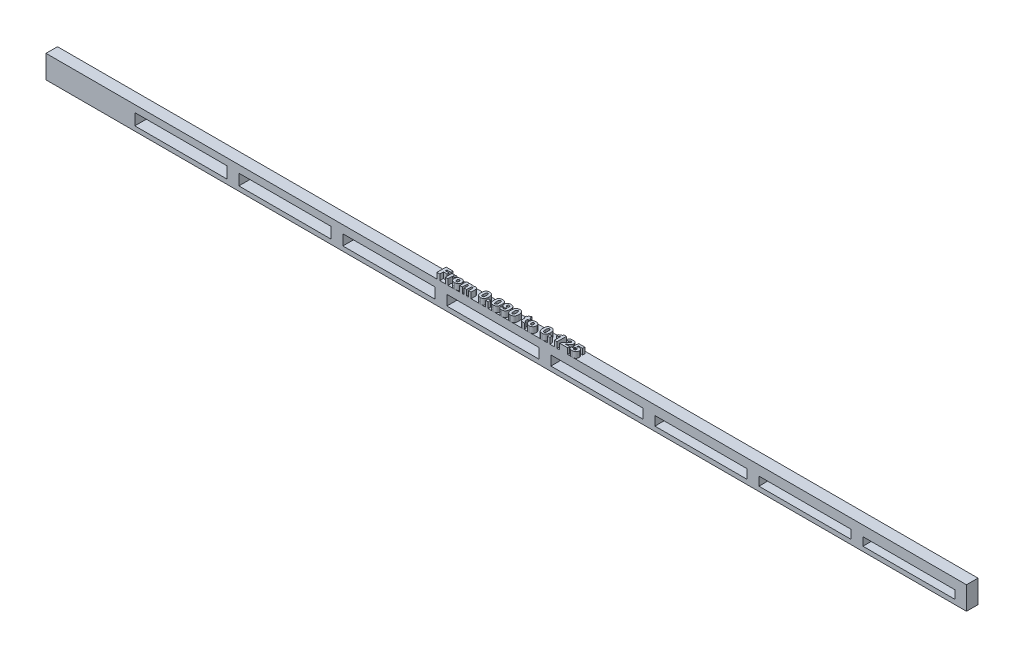
SolidWorks part; units mm, degrees
ref_plane "Front Plane" through (0, 0, 0) normal (0, 0, 1) x (1, 0, 0)
ref_plane "Top Plane" through (0, 0, 0) normal (0, 1, 0) x (1, 0, 0)
ref_plane "Right Plane" through (0, 0, 0) normal (1, 0, 0) x (0, 0, -1)
sketch "Sketch1" plane through (0, 0, 0) normal (0, 1, 0) x (1, 0, 0)
  line L1 (-127, -1.5875) -> (127, -1.5875)
  line L2 (-127, -1.5875) -> (-127, 1.5875)
  line L3 (-127, 1.5875) -> (127, 1.5875)
  line L4 (127, -1.5875) -> (127, 1.5875)
  line L5 (-127, -1.5875) -> (127, 1.5875) construction
  line L6 (-127, 1.5875) -> (127, -1.5875) construction
  point P0 (0, 0)
  dimension "D1" = 3.175
  dimension "D2" = 254
extrude "Boss-Extrude1" add sketch "Sketch1" along normal mid plane 6.35
sketch "Sketch2" plane through (0, 0, 0) normal (0, 0, 1) x (1, 0, 0)
  line L0 (127, 3.175) -> (127, -3.175) construction
  line L1 (123.825, 0.381) -> (98.425, 0.381)
  line L2 (123.825, 0.381) -> (123.825, -1.905)
  line L3 (123.825, -1.905) -> (98.425, -1.905)
  line L4 (98.425, 0.381) -> (98.425, -1.905)
  line L5 (95.123, 0.508) -> (69.723, 0.508)
  line L6 (95.123, 0.508) -> (95.123, -1.905)
  line L7 (95.123, -1.905) -> (69.723, -1.905)
  line L8 (69.723, 0.508) -> (69.723, -1.905)
  line L9 (66.421, 0.635) -> (41.021, 0.635)
  line L10 (66.421, 0.635) -> (66.421, -1.905)
  line L11 (66.421, -1.905) -> (41.021, -1.905)
  line L12 (41.021, 0.635) -> (41.021, -1.905)
  line L13 (37.719, 0.762) -> (12.319, 0.762)
  line L14 (37.719, 0.762) -> (37.719, -1.905)
  line L15 (37.719, -1.905) -> (12.319, -1.905)
  line L16 (12.319, 0.762) -> (12.319, -1.905)
  line L17 (9.017, 0.889) -> (-16.383, 0.889)
  line L18 (9.017, 0.889) -> (9.017, -1.905)
  line L19 (9.017, -1.905) -> (-16.383, -1.905)
  line L20 (-16.383, 0.889) -> (-16.383, -1.905)
  line L21 (-19.685, 1.016) -> (-45.085, 1.016)
  line L22 (-19.685, 1.016) -> (-19.685, -1.905)
  line L23 (-19.685, -1.905) -> (-45.085, -1.905)
  line L24 (-45.085, 1.016) -> (-45.085, -1.905)
  line L25 (-48.387, 1.143) -> (-73.787, 1.143)
  line L26 (-48.387, 1.143) -> (-48.387, -1.905)
  line L27 (-48.387, -1.905) -> (-73.787, -1.905)
  line L28 (-73.787, 1.143) -> (-73.787, -1.905)
  line L29 (-77.089, 1.27) -> (-102.489, 1.27)
  line L30 (-77.089, 1.27) -> (-77.089, -1.905)
  line L31 (-77.089, -1.905) -> (-102.489, -1.905)
  line L32 (-102.489, 1.27) -> (-102.489, -1.905)
  line L33 (127, -3.175) -> (-127, -3.175) construction
  dimension "D1" = 25.4
  dimension "D2" = 3.175
  dimension "D4" = 2.286
  dimension "D5" = 2.54
  dimension "D3" = 2.413
  dimension "D6" = 2.667
  dimension "D7" = 2.794
  dimension "D8" = 2.921
  dimension "D9" = 3.048
  dimension "D10" = 3.175
  dimension "D11" = 1.27
extrude "Cut-Extrude1" cut sketch "Sketch2" against normal through all both and the other way through all
sketch "Sketch4" plane through (0, 3.175, 0) normal (0, 1, 0) x (1, 0, 0)
  text T0 "<b>From 0.090 to 0.125</b>" font "Arial Black" height 2.54
extrude "Boss-Extrude2" add sketch "Sketch4" along normal blind 1.5875
